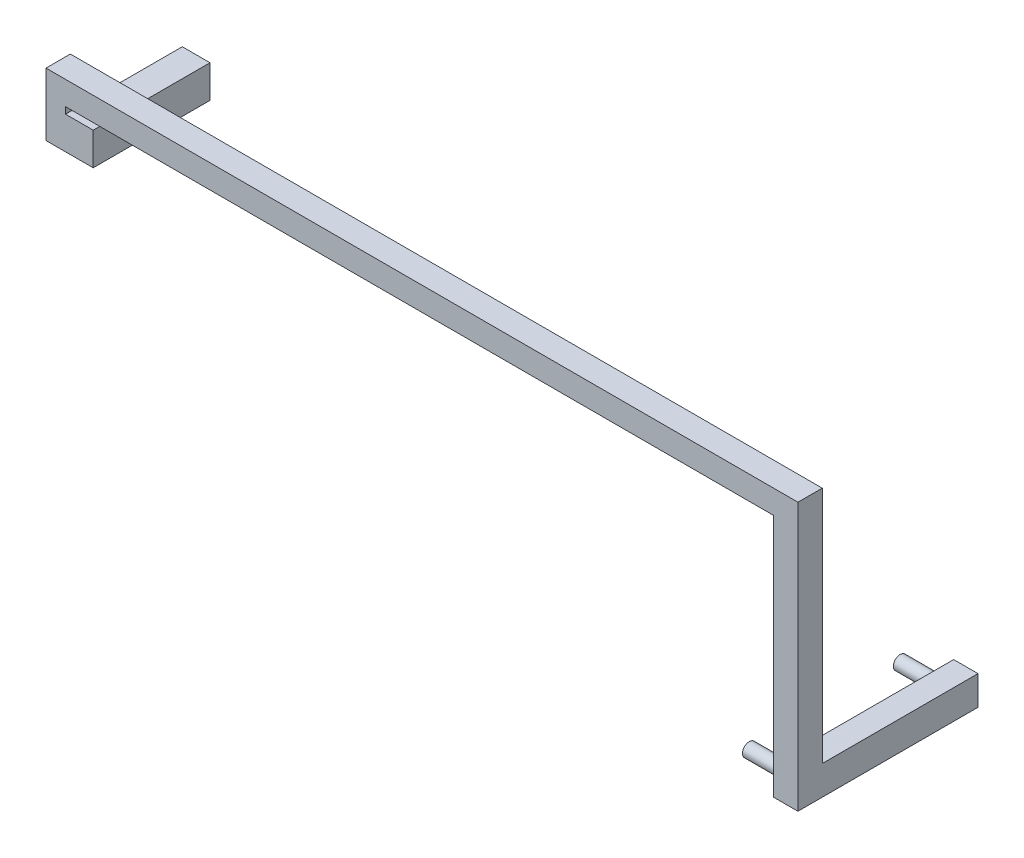
SolidWorks part; units mm, degrees
ref_plane "Front Plane" through (0, 0, 0) normal (0, 0, 1) x (1, 0, 0)
ref_plane "Top Plane" through (0, 0, 0) normal (0, 1, 0) x (1, 0, 0)
ref_plane "Right Plane" through (0, 0, 0) normal (1, 0, 0) x (0, 0, -1)
sketch "Sketch1" plane through (0, 0, 0) normal (0, 0, 1) x (1, 0, 0)
  line L0 (0, 6.7) -> (0, 8.05)
  line L1 (0, 0) -> (5.7, 0)
  line L3 (0, 6.7) -> (5.7, 6.7)
  line L4 (5.7, 0) -> (5.7, 6.7)
  line L5 (0, 0) -> (-4, 0)
  line L6 (-4, 0) -> (-4, 12.9)
  line L7 (-4, 12.9) -> (5.5, 12.9)
  line L8 (0, 8.05) -> (5.5, 8.05)
  line L10 (5.5, 12.9) -> (150.5, 12.9)
  line L11 (5.5, 8.05) -> (145.5, 8.05)
  line L12 (150.5, 8.05) -> (150.5, 12.9)
  line L13 (150.5, 8.05) -> (150.5, -42.1)
  line L14 (145.5, 8.05) -> (145.5, -42.1)
  line L15 (145.5, -42.1) -> (150.5, -42.1)
  dimension "D1" = 6.7
  dimension "D2" = 5.7
  dimension "D3" = 1.35
  dimension "D4" = 4
  dimension "D5" = 4.85
  dimension "D6" = 9.5
  dimension "D7" = 5.5
  dimension "D8" = 4.85
  dimension "D9" = 145
  dimension "D10" = 145
  dimension "D11" = 4.85
  dimension "D12" = 55
  dimension "D14" = 5
  dimension "D15" = 5
extrude "Boss-Extrude1" add sketch "Sketch1" along normal blind 5
sketch "Sketch2" plane through (0, 0, 5) normal (0, 0, 1) x (1, 0, 0)
  line L1 (5.7, 6.7) -> (0, 6.7)
  line L2 (5.7, 6.7) -> (5.7, 0)
  line L3 (5.7, 0) -> (0, 0)
  line L4 (0, 6.7) -> (0, 0)
extrude "Boss-Extrude6" add sketch "Sketch2" against normal blind 24
sketch "Sketch5" plane through (0, 0, 0) normal (0, 0, -1) x (-1, 0, 0)
  line L0 (-145.5, 8.05) -> (-145.5, -42.1) construction
  line L1 (-150.5, -42.1) -> (-145.5, -42.1)
  line L2 (-150.5, -42.1) -> (-150.5, -36.1)
  line L3 (-150.5, -36.1) -> (-145.5, -36.1)
  line L4 (-145.5, -42.1) -> (-145.5, -36.1)
extrude "Boss-Extrude7" add sketch "Sketch5" along normal blind 32
sketch "Sketch4" plane through (145.5, 0, 0) normal (-1, 0, 0) x (0, 0, 1)
  line L0 (-32, -36.1) -> (0, -36.1) construction
  line L2 (-32, -42.1) -> (-32, -36.1) construction
  circle A2 centre (-29, -39.1) radius 1.4
  circle A3 centre (2, -39.1) radius 1.4
  dimension "D7" = 2.8
  dimension "D8" = 2.8
  dimension "D9" = 31
  dimension "D10" = 3
  dimension "D11" = 3
  dimension "D12" = 3
extrude "Boss-Extrude4" add sketch "Sketch4" along normal blind 8
